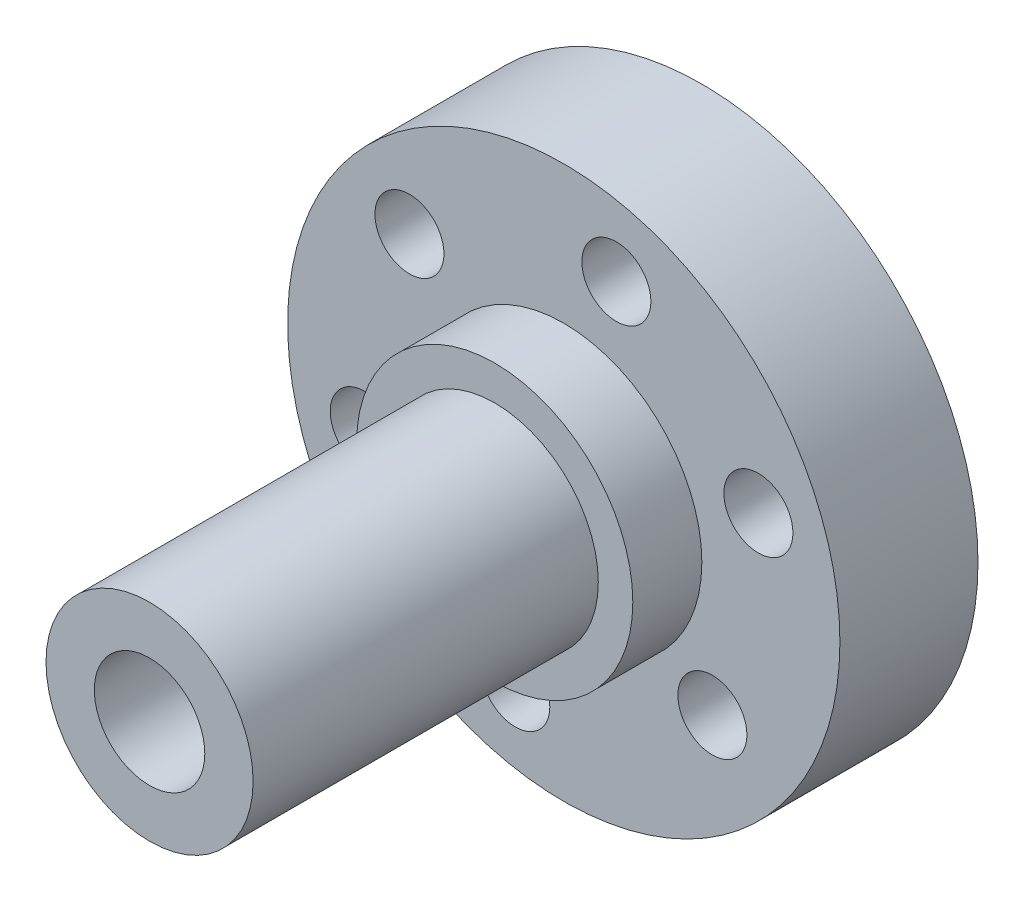
SolidWorks part; units mm, degrees
ref_plane "Front Plane" through (0, 0, 0) normal (0, 0, 1) x (1, 0, 0)
ref_plane "Top Plane" through (0, 0, 0) normal (0, 1, 0) x (1, 0, 0)
ref_plane "Right Plane" through (0, 0, 0) normal (1, 0, 0) x (0, 0, -1)
sketch "Sketch1" plane through (0, 0, 0) normal (0, 0, 1) x (1, 0, 0)
  line L0 (3.8092, 14.5083) -> (0, 0) construction
  circle A0 centre (0, 0) radius 20
  circle A1 centre (0, 0) radius 15 construction
  circle A2 centre (3.8092, 14.5083) radius 2.5
  circle A3 centre (14.0954, 5.1302) radius 2.5
  circle A4 centre (10.7636, -9.2028) radius 2.5
  circle A5 centre (-3.5113, -14.5832) radius 2.5
  circle A6 centre (-14.4158, -3.9837) radius 2.5
  circle A7 centre (-11.1789, 10.0016) radius 2.5
  dimension "D1" = 30
  dimension "D2" = 5
  dimension "D3" = 13.9195
  dimension "D4" = 40
  dimension "D5" = 14.1614
extrude "Boss-Extrude1" add sketch "Sketch1" along normal blind 10
sketch "Sketch2" plane through (0, 0, 10) normal (0, 0, 1) x (1, 0, 0)
  circle A0 centre (0, 0) radius 7.5
  dimension "D1" = 15
extrude "Boss-Extrude2" add sketch "Sketch2" along normal blind 30
sketch "Sketch3" plane through (0, 0, 40) normal (0, 0, 1) x (1, 0, 0)
  circle A0 centre (0, 0) radius 4
  dimension "D1" = 8
extrude "Cut-Extrude1" cut sketch "Sketch3" against normal blind 30
sketch "Sketch4" plane through (0, 0, 0) normal (0, 0, -1) x (-1, 0, 0)
  line L1 (-1.5, 1.5) -> (1.5, 1.5)
  line L2 (-1.5, 1.5) -> (-1.5, -1.5)
  line L3 (-1.5, -1.5) -> (1.5, -1.5)
  line L4 (1.5, 1.5) -> (1.5, -1.5)
  line L5 (-1.5, 1.5) -> (1.5, -1.5) construction
  line L6 (-1.5, -1.5) -> (1.5, 1.5) construction
  point P0 (0, 0)
  dimension "D1" = 3
  dimension "D2" = 3
extrude "Cut-Extrude2" cut sketch "Sketch4" against normal blind 20
sketch "Sketch5" plane through (0, 0, 10) normal (0, 0, 1) x (1, 0, 0)
  circle A0 centre (0, 0) radius 10
  circle A1 centre (0, 0) radius 7.5
  dimension "D1" = 20
extrude "Boss-Extrude3" add sketch "Sketch5" along normal blind 5
